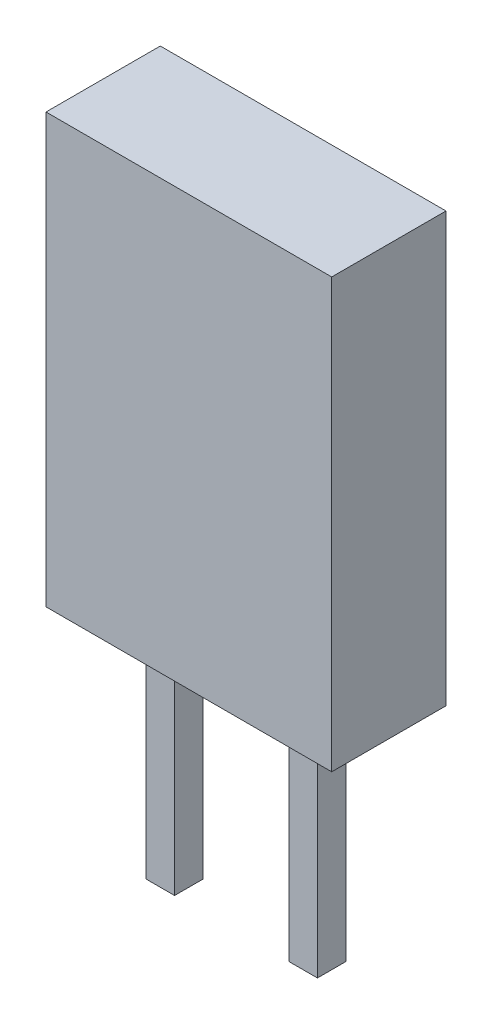
SolidWorks part; units mm, degrees
ref_plane "前视基准面" through (0, 0, 0) normal (0, 0, 1) x (1, 0, 0)
ref_plane "上视基准面" through (0, 0, 0) normal (0, 1, 0) x (1, 0, 0)
ref_plane "右视基准面" through (0, 0, 0) normal (1, 0, 0) x (0, 0, -1)
sketch "草图1" plane through (0, 0, 0) normal (0, 0, 1) x (1, 0, 0)
  line L1 (-2.5, -3.75) -> (2.5, -3.75)
  line L2 (-2.5, -3.75) -> (-2.5, 3.75)
  line L3 (-2.5, 3.75) -> (2.5, 3.75)
  line L4 (2.5, -3.75) -> (2.5, 3.75)
  line L5 (-2.5, -3.75) -> (2.5, 3.75) construction
  line L6 (-2.5, 3.75) -> (2.5, -3.75) construction
  point P0 (0, 0)
  dimension "D1" = 5
  dimension "D2" = 7.5
extrude "凸台-拉伸1" add sketch "草图1" along normal mid plane 2
sketch "草图3" plane through (0, 0, 0) normal (0, 0, 1) x (1, 0, 0)
  line L0 (1.5, -3.75) -> (1.5, -1.95)
  line L1 (-2.5, -3.75) -> (2.5, -3.75) construction
  line L2 (0.5, -1.95) -> (1, -1.95)
  line L3 (1.3, -1.75) -> (1.3, 0.25)
  line L4 (1.3, 0.25) -> (-1.2, 0.25)
  line L5 (-1.2, 0.25) -> (0.5, -1.95)
  line L6 (1.3, -1.75) -> (1.5, -1.95)
  line L7 (1, -1.95) -> (1, -3.75)
  line L8 (-1.5, -3.75) -> (-1.5, -7.75)
  line L9 (-1.3, 0.25) -> (-1.3, -1.75)
  line L10 (-1.3, -1.75) -> (-1.5, -1.95)
  line L11 (-1.5, -1.95) -> (-1.5, -3.75)
  line L12 (-1.5, -7.75) -> (-1, -7.75)
  line L13 (-1, -3.75) -> (-1, -1.95)
  line L14 (-1, -1.95) -> (-0.2, -1.75)
  line L15 (-0.2, -1.75) -> (-1.3, 0.25)
  line L16 (-1.25, -3.0193) -> (-1.25, -4.4807) construction
  line L17 (1.25, -2.9335) -> (1.25, -4.5665) construction
  line L18 (-1, -7.75) -> (-1, -3.75)
  line L19 (1, -3.75) -> (1, -7.75)
  line L20 (1, -7.75) -> (1.5, -7.75)
  line L21 (1.5, -7.75) -> (1.5, -3.75)
  point P12 (-0.7, 0.25)
  point P20 (1.25, -3.75)
  point P23 (-1.25, -3.75)
  point P26 (0, -1.95)
  dimension "D1" = 4
  dimension "D2" = 0.5
  dimension "D3" = 0.5
  dimension "D4" = 2.5
  dimension "D5" = 1.25
  dimension "D6" = 0.2
  dimension "D7" = 0.2
  dimension "D8" = 2
  dimension "D9" = 2.5
  dimension "D10" = 0.2
  dimension "D11" = 1.3
  dimension "D12" = 4
  dimension "D13" = 4
  dimension "D14" = 0.5
extrude "凸台-拉伸2" add sketch "草图3" along normal mid plane 0.5 separate body
fillet "圆角1" radius 0.2 4 edges at (1.3, -1.75, 0) (1.5, -1.95, 0) (1, -1.95, 0) (0.5, -1.95, 0)
fillet "圆角2" radius 0.2 3 edges at (-1.3, -1.75, 0) (-1.5, -1.95, 0) (-1, -1.95, 0)
